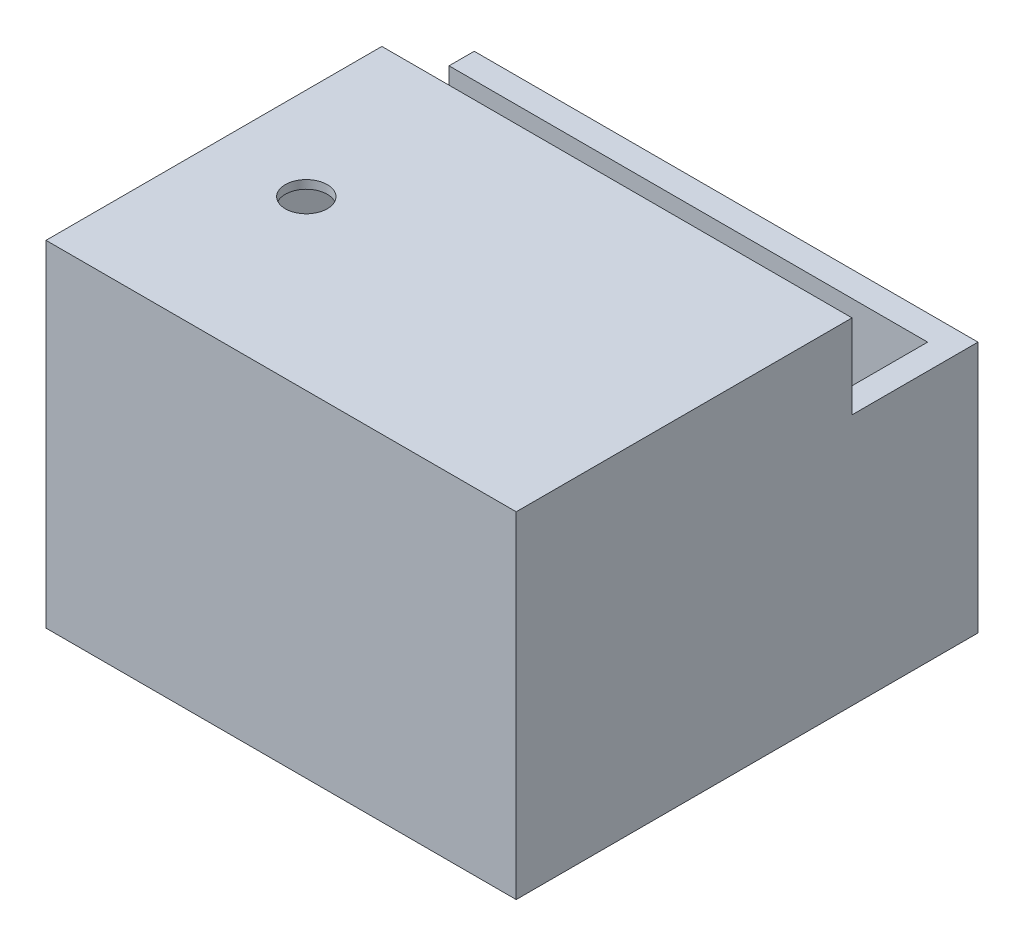
SolidWorks part; units mm, degrees
ref_plane "Front Plane" through (0, 0, 0) normal (0, 0, 1) x (1, 0, 0)
ref_plane "Top Plane" through (0, 0, 0) normal (0, 1, 0) x (1, 0, 0)
ref_plane "Right Plane" through (0, 0, 0) normal (1, 0, 0) x (0, 0, -1)
sketch "Sketch1" plane through (0, 0, 0) normal (0, 1, 0) x (1, 0, 0)
  line L0 (0, 0) -> (60, 0)
  line L1 (60, 0) -> (60, -15)
  dimension "D1" = 60
  dimension "D2" = 15
extrude "Extrude-Thin1" add sketch "Sketch1" along normal blind 30 thin
sketch "Sketch2" plane through (0, 0, 3) normal (0, 0, 1) x (1, 0, 0)
  line L0 (0, 0) -> (30, 30) construction
  line L1 (0, 30) -> (57, 30) construction
  line L2 (0, 30) -> (0, 0) construction
  circle A0 centre (15, 15) radius 4.1
  dimension "D2" = 8.2
  dimension "D1" = 45
extrude "Cut-Extrude1" cut sketch "Sketch2" against normal blind 10
sketch "Sketch3" plane through (57, 0, 0) normal (-1, 0, 0) x (0, 0, 1)
  line L1 (15, 0) -> (55, 0)
  line L2 (15, 0) -> (15, 40)
  line L3 (15, 40) -> (55, 40)
  line L4 (55, 0) -> (55, 40)
  dimension "D1" = 40
extrude "Boss-Extrude1" add sketch "Sketch3" along normal blind 15 from vertex at -3 starting at point (60, 30, 15)
sketch "Sketch4" plane through (45, 0, 0) normal (-1, 0, 0) x (0, 0, 1)
  line L0 (15, 0) -> (55, 40) construction
  circle A0 centre (35, 20) radius 6
  dimension "D1" = 12
extrude "Boss-Extrude2" add sketch "Sketch4" along normal blind 5
fillet "Fillet1" radius 2 1 edges at (45, 20, 29)
sketch "Sketch5" plane through (45, 0, 0) normal (-1, 0, 0) x (0, 0, 1)
  line L4 (15, 40) -> (15, 0)
  line L5 (15, 0) -> (55, 0)
  line L6 (55, 0) -> (55, 40)
  line L7 (55, 40) -> (15, 40)
  line L8 (15, 40) -> (15, 0)
  line L9 (15, 0) -> (55, 0)
  line L10 (55, 0) -> (55, 40)
  line L11 (55, 40) -> (15, 40)
  line L16 (16, 39) -> (16, 1)
  line L17 (16, 1) -> (54, 1)
  line L18 (54, 1) -> (54, 39)
  line L19 (54, 39) -> (16, 39)
  line L20 (16, 39) -> (16, 1)
  line L21 (16, 1) -> (54, 1)
  line L22 (54, 1) -> (54, 39)
  line L23 (54, 39) -> (16, 39)
  dimension "D1" = 0
  dimension "D2" = 1
extrude "Boss-Extrude3" add sketch "Sketch5" along normal blind 40
sketch "Sketch6" plane through (5, 0, 0) normal (-1, 0, 0) x (0, 0, 1)
  line L4 (55, 40) -> (15, 40)
  line L5 (15, 40) -> (15, 0)
  line L6 (15, 0) -> (55, 0)
  line L7 (55, 0) -> (55, 40)
  line L8 (55, 40) -> (15, 40)
  line L9 (15, 40) -> (15, 0)
  line L10 (15, 0) -> (55, 0)
  line L11 (55, 0) -> (55, 40)
  dimension "D1" = 0
extrude "Boss-Extrude4" add sketch "Sketch6" along normal blind 1
sketch "Sketch7" plane through (0, 40, 0) normal (0, 1, 0) x (1, 0, 0)
  line L0 (15, -3) -> (15, -35) construction
  line L1 (10.9, -3) -> (19.1, -3) construction
  line L2 (4, -35) -> (15, -35) construction
  line L3 (4, -55) -> (4, -15) construction
  circle A0 centre (15, -35) radius 2.5
  dimension "D1" = 5
extrude "Cut-Extrude2" cut sketch "Sketch7" against normal through all
ref_point "Point1"
ref_plane "Plane1" through (0, 0, 35) normal (0, 0, 1) x (1, 0, 0)
sketch "Sketch8" plane through (0, 0, 35) normal (0, 0, 1) x (1, 0, 0)
  line L0 (17.5, 1) -> (22.9667, 8.1495)
  line L1 (22.9667, 8.1495) -> (23.9667, 8.1495)
  line L2 (23.9667, 8.1495) -> (23.9667, 1)
  line L3 (5, 1) -> (45, 1) construction
  line L4 (23.9667, 1) -> (17.5, 1)
  line L5 (15, 1) -> (15, 17.7827) construction
  dimension "D1" = 9
  dimension "D2" = 7.1495
  dimension "D3" = 1
revolve "Revolve1" add sketch "Sketch8" angle 360 about L5
